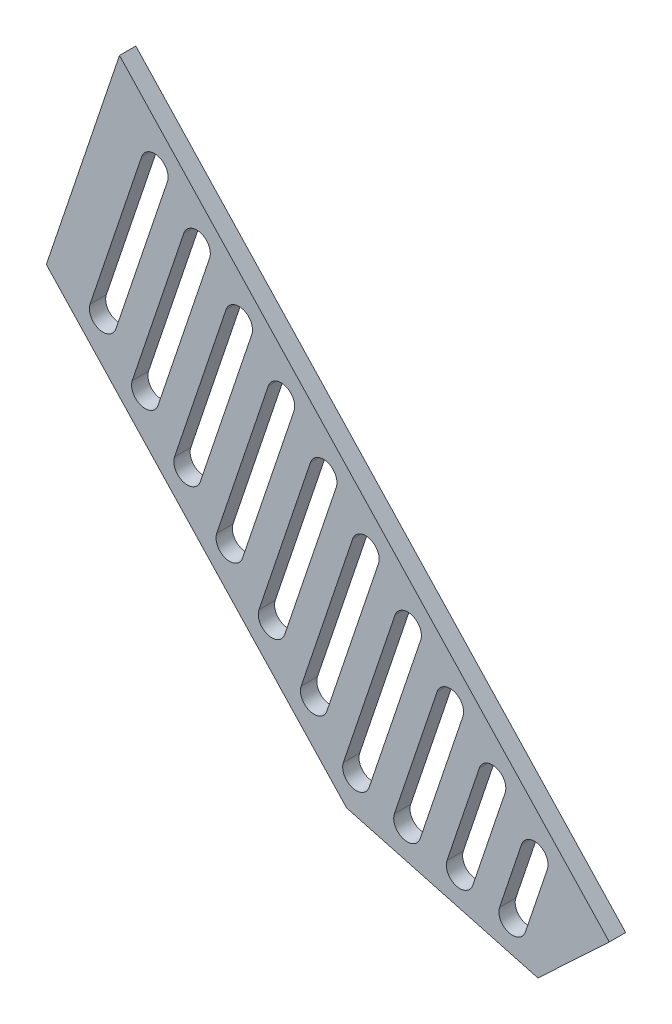
SolidWorks part; units mm, degrees
ref_plane "Front Plane" through (0, 0, 0) normal (1, 0, 0) x (0, 1, 0)
ref_plane "Top Plane" through (0, 0, 0) normal (0, 0, 1) x (0, 1, 0)
ref_plane "Right Plane" through (0, 0, 0) normal (0, 1, 0) x (-1, 0, 0)
sketch "Sketch1" plane through (766.4793, -257.6169, 0) normal (0, 0, 1) x (0.2605, 0.9655, 0)
  line L15 (33.7721, 853.0418) -> (33.7721, 816.601)
  line L16 (33.7721, 816.601) -> (49.0751, 807.1237)
  line L17 (49.0751, 807.1237) -> (118.4535, 919.1497)
  line L18 (118.4535, 919.1497) -> (76.3005, 921.7127)
  line L19 (76.3005, 921.7127) -> (33.7721, 853.0418)
  point P0 (0, 0)
  dimension "D1" = 118.291
  dimension "D2" = 148.23
  dimension "D3" = 80.7735
  dimension "D4" = 36.4408
  dimension "D5" = 18
extrude "Boss-Extrude1" add sketch "Sketch1" along normal blind 3
sketch "Sketch2" plane through (0, 0, 3) normal (0, 0, 1) x (0.2605, 0.9655, 0)
  line L0 (20.8413, 91.5842) -> (50.5253, 89.7793)
  line L7 (21.1448, 96.5749) -> (50.8287, 94.7701)
  line L8 (20.993, 94.0795) -> (50.677, 92.2747) construction
  line L9 (14.862, 81.9292) -> (44.5459, 80.1244)
  line L10 (15.1654, 86.92) -> (44.8494, 85.1152)
  line L11 (26.9724, 103.7345) -> (56.6563, 101.9296) construction
  line L12 (27.1241, 106.2299) -> (56.8081, 104.425)
  line L13 (26.8207, 101.2391) -> (56.5046, 99.4342)
  line L14 (15.0137, 84.4246) -> (44.6976, 82.6198) construction
  line L15 (8.8826, 72.2743) -> (38.5666, 70.4695)
  line L16 (9.1861, 77.2651) -> (38.87, 75.4603)
  line L17 (9.0343, 74.7697) -> (38.7183, 72.9649) construction
  line L18 (2.9033, 62.6194) -> (32.5872, 60.8146)
  line L19 (3.2067, 67.6102) -> (32.8907, 65.8054)
  line L20 (3.055, 65.1148) -> (32.739, 63.31) construction
  line L21 (-3.0761, 52.9645) -> (26.6079, 51.1597)
  line L22 (-2.7726, 57.9553) -> (26.9113, 56.1504)
  line L23 (-2.9243, 55.4599) -> (26.7596, 53.6551) construction
  line L24 (28.8322, 111.4858) -> (-12.303, 45.0643)
  line L25 (-12.303, 45.0643) -> (-12.303, 11.148)
  line L26 (-12.303, 11.148) -> (-0.971, 4.13)
  line L27 (-0.971, 4.13) -> (64.1839, 109.3363)
  line L28 (64.1839, 109.3363) -> (28.8322, 111.4858)
  line L29 (28.8322, 111.4858) -> (-12.303, 45.0643) construction
  line L30 (-12.303, 45.0643) -> (-12.303, 11.148) construction
  line L31 (-12.303, 11.148) -> (-0.971, 4.13) construction
  line L32 (-0.971, 4.13) -> (64.1839, 109.3363) construction
  line L33 (64.1839, 109.3363) -> (28.8322, 111.4858) construction
  line L34 (-9.0554, 43.3096) -> (20.6285, 41.5048)
  line L35 (-8.752, 48.3004) -> (20.932, 46.4955)
  line L36 (-8.9037, 45.805) -> (20.7803, 44.0001) construction
  line L39 (-9.803, 15.8043) -> (2.8422, 15.0354) construction
  line L40 (-9.803, 35.8412) -> (14.8009, 34.3452) construction
  line L41 (-9.6513, 38.3366) -> (14.9526, 36.8406)
  line L42 (-9.9547, 33.3458) -> (14.6492, 31.8498)
  line L43 (-9.803, 25.8228) -> (8.8216, 24.6903) construction
  line L44 (-9.6513, 28.3181) -> (8.9733, 27.1857)
  line L45 (-9.9547, 23.3274) -> (8.6698, 22.1949)
  line L46 (-14.7313, 38.6455) -> (14.9526, 36.8406) [skipped]
  line L47 (-15.0348, 33.6547) -> (14.6492, 31.8498) [skipped]
  line L48 (-9.6513, 18.2997) -> (2.9939, 17.5308)
  line L49 (-9.9547, 13.3089) -> (2.6905, 12.54)
  line L50 (-3.6321, 12.9245) -> (-6.831, 7.7592) construction
  line L53 (41.9661, 105.3274) -> (45.165, 110.4927) construction
  arc A0 (27.1241, 106.2299) -> (26.8207, 101.2391) centre (26.9724, 103.7345) ccw
  arc A1 (56.5046, 99.4342) -> (56.8081, 104.425) centre (56.6563, 101.9296) ccw
  arc A2 (21.1448, 96.5749) -> (20.8413, 91.5842) centre (20.993, 94.0795) ccw
  arc A3 (50.5253, 89.7793) -> (50.8287, 94.7701) centre (50.677, 92.2747) ccw
  arc A4 (15.1654, 86.92) -> (14.862, 81.9292) centre (15.0137, 84.4246) ccw
  arc A5 (44.5459, 80.1244) -> (44.8494, 85.1152) centre (44.6976, 82.6198) ccw
  arc A6 (9.1861, 77.2651) -> (8.8826, 72.2743) centre (9.0343, 74.7697) ccw
  arc A7 (38.5666, 70.4695) -> (38.87, 75.4603) centre (38.7183, 72.9649) ccw
  arc A8 (3.2067, 67.6102) -> (2.9033, 62.6194) centre (3.055, 65.1148) ccw
  arc A9 (32.5872, 60.8146) -> (32.8907, 65.8054) centre (32.739, 63.31) ccw
  arc A10 (-2.7726, 57.9553) -> (-3.0761, 52.9645) centre (-2.9243, 55.4599) ccw
  arc A11 (26.6079, 51.1597) -> (26.9113, 56.1504) centre (26.7596, 53.6551) ccw
  arc A12 (-8.752, 48.3004) -> (-9.0554, 43.3096) centre (-8.9037, 45.805) ccw
  arc A13 (20.6285, 41.5048) -> (20.932, 46.4955) centre (20.7803, 44.0001) ccw
  arc A16 (-9.6513, 38.3366) -> (-9.9547, 33.3458) centre (-9.803, 35.8412) ccw
  arc A17 (14.6492, 31.8498) -> (14.9526, 36.8406) centre (14.8009, 34.3452) ccw
  arc A18 (-9.6513, 28.3181) -> (-9.9547, 23.3274) centre (-9.803, 25.8228) ccw
  arc A19 (8.6698, 22.1949) -> (8.9733, 27.1857) centre (8.8216, 24.6903) ccw
  arc A20 (-14.7313, 38.6455) -> (-15.0348, 33.6547) centre (-14.883, 36.1501) ccw [skipped]
  arc A21 (14.6492, 31.8498) -> (14.9526, 36.8406) centre (14.8009, 34.3452) ccw [skipped]
  arc A22 (-9.6513, 18.2997) -> (-9.9547, 13.3089) centre (-9.803, 15.8043) ccw
  arc A23 (2.6905, 12.54) -> (2.9939, 17.5308) centre (2.8422, 15.0354) ccw
  point P2 (41.8144, 102.832)
  point P10 (35.835, 93.1771)
  point P19 (29.8557, 83.5222)
  point P29 (23.8763, 73.8673)
  point P36 (17.897, 64.2124)
  point P43 (11.9176, 54.5575)
  point P50 (5.9383, 44.9026)
  point P55 (-3.4804, 15.4199)
  point P63 (2.499, 35.0932)
  point P70 (-0.4907, 25.2565)
  dimension "D1" = 3
  dimension "D2" = 8
  dimension "D3" = 5
  dimension "D4" = 5
  dimension "D5" = 5
  dimension "D6" = 5
  dimension "D7" = 5
  dimension "D8" = 5
  dimension "D9" = 5
  dimension "D10" = 5
extrude "Cut-Extrude1" cut sketch "Sketch2" against normal blind 3
